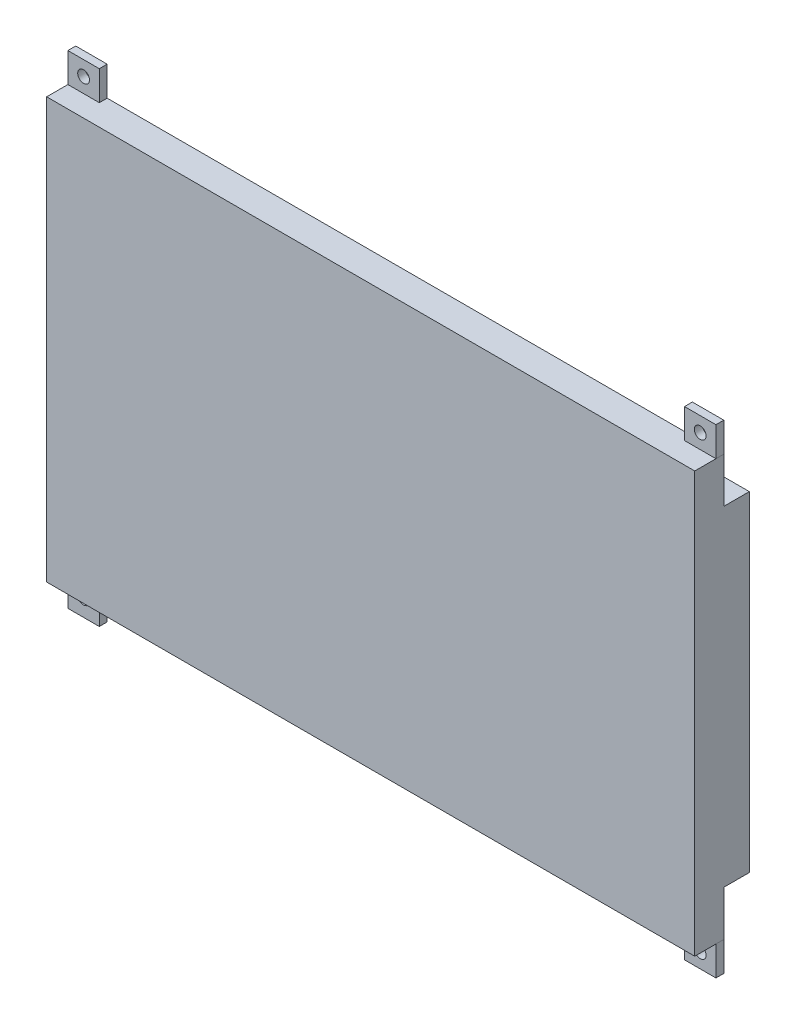
SolidWorks part; units mm, degrees
ref_plane "Front Plane" through (0, 0, 0) normal (0, 0, 1) x (1, 0, 0)
ref_plane "Top Plane" through (0, 0, 0) normal (0, 1, 0) x (1, 0, 0)
ref_plane "Right Plane" through (0, 0, 0) normal (1, 0, 0) x (0, 0, -1)
sketch "Sketch1" plane through (0, 0, 0) normal (0, 0, 1) x (1, 0, 0)
  line L5 (-82.5, 53.5) -> (82.5, 53.5)
  line L6 (-82.5, 53.5) -> (-82.5, -53.5)
  line L23 (-82.5, -53.5) -> (82.5, -53.5)
  line L24 (82.5, 53.5) -> (82.5, -53.5)
  line L25 (-82.5, 53.5) -> (82.5, -53.5) construction
  line L26 (-82.5, -53.5) -> (82.5, 53.5) construction
  point P0 (0, 0)
  dimension "D1" = 165
  dimension "D2" = 107
extrude "Boss-Extrude1" add sketch "Sketch1" along normal blind 7.4
sketch "Sketch2" plane through (0, 0, 0) normal (0, 0, -1) x (-1, 0, 0)
  line L0 (-74.5, 61) -> (-82.5, 53.5) construction
  line L1 (-82.5, 53.5) -> (-74.5, 53.5)
  line L2 (-82.5, 53.5) -> (-82.5, 61)
  line L3 (-82.5, 61) -> (-74.5, 61)
  line L4 (-74.5, 53.5) -> (-74.5, 61)
  line L5 (82.5, 53.5) -> (74.5, 53.5)
  line L6 (82.5, 53.5) -> (82.5, 61)
  line L7 (82.5, 61) -> (74.5, 61)
  line L8 (74.5, 53.5) -> (74.5, 61)
  line L9 (82.5, -53.5) -> (74.5, -53.5)
  line L10 (82.5, -53.5) -> (82.5, -62)
  line L11 (82.5, -62) -> (74.5, -62)
  line L12 (74.5, -53.5) -> (74.5, -62)
  line L13 (-82.5, -53.5) -> (-74.5, -53.5)
  line L14 (-82.5, -53.5) -> (-82.5, -61)
  line L15 (-82.5, -61) -> (-74.5, -61)
  line L16 (-74.5, -53.5) -> (-74.5, -61)
  line L17 (82.5, 61) -> (74.5, 53.5) construction
  line L18 (-74.5, -61) -> (-82.5, -53.5) construction
  line L19 (82.5, -53.5) -> (74.5, -62) construction
  circle A0 centre (-78.5, 57.25) radius 1.5
  circle A1 centre (78.5, 57.25) radius 1.5
  circle A2 centre (-78.5, -57.25) radius 1.5
  circle A3 centre (78.5, -57.75) radius 1.5
  point P22 (-82.5, 64.0745)
  point P23 (74.8756, 53.25)
  point P26 (82.9141, -53.25)
  point P27 (-84.9188, -53.25)
  point P30 (82.5, 61.4174)
  point P31 (74.9178, -61.75)
  point P34 (-63.1452, -53.25)
  point P35 (-76.3483, -61.75)
  dimension "D3" = 3
  dimension "D1" = 157
  dimension "D2" = 114.5
extrude "Boss-Extrude2" add sketch "Sketch2" against normal blind 2 separate body
sketch "Sketch3" plane through (0, 0, 0) normal (0, 0, -1) x (-1, 0, 0)
  line L0 (-82.5, -53.5) -> (-82.5, 53.5) construction
  line L1 (-82.5, 42) -> (82.5, 42)
  line L2 (-82.5, 42) -> (-82.5, -42)
  line L3 (-82.5, -42) -> (82.5, -42)
  line L4 (82.5, 42) -> (82.5, -42)
  line L5 (82.5, 53.5) -> (82.5, -53.5) construction
  point P6 (82.5, 0)
  point P8 (82.5, -42)
  dimension "D1" = 84
extrude "Boss-Extrude3" add sketch "Sketch3" along normal blind 6.5
